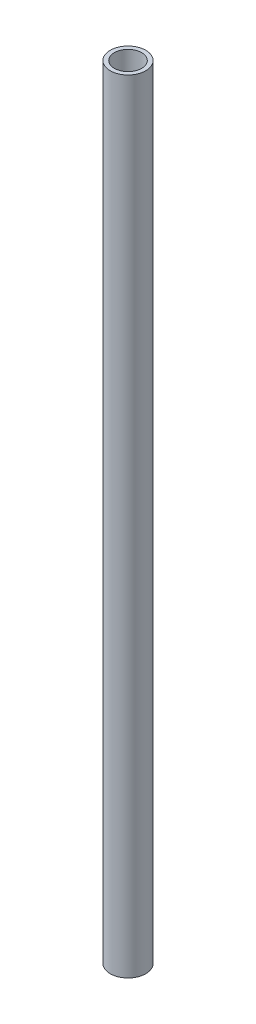
SolidWorks part; units mm, degrees
material "AISI 4130 Steel, annealed at 865C"
ref_plane "X-Y Datum" through (0, 0, 0) normal (0, 0, 1) x (1, 0, 0)
ref_plane "X-Z Datum" through (0, 0, 0) normal (0, 1, 0) x (1, 0, 0)
ref_plane "Y-Z Datum" through (0, 0, 0) normal (1, 0, 0) x (0, 0, -1)
sketch "Sketch1" plane through (0, 0, 0) normal (0, 1, 0) x (1, 0, 0)
  circle A0 centre (0, 0) radius 6.35
  circle A1 centre (0, 0) radius 4.8768
  dimension "D1" = 12.7
  dimension "D2" = 1.4732
extrude "Boss-Extrude1" add sketch "Sketch1" along normal up to surface (279.5232 mm away)
